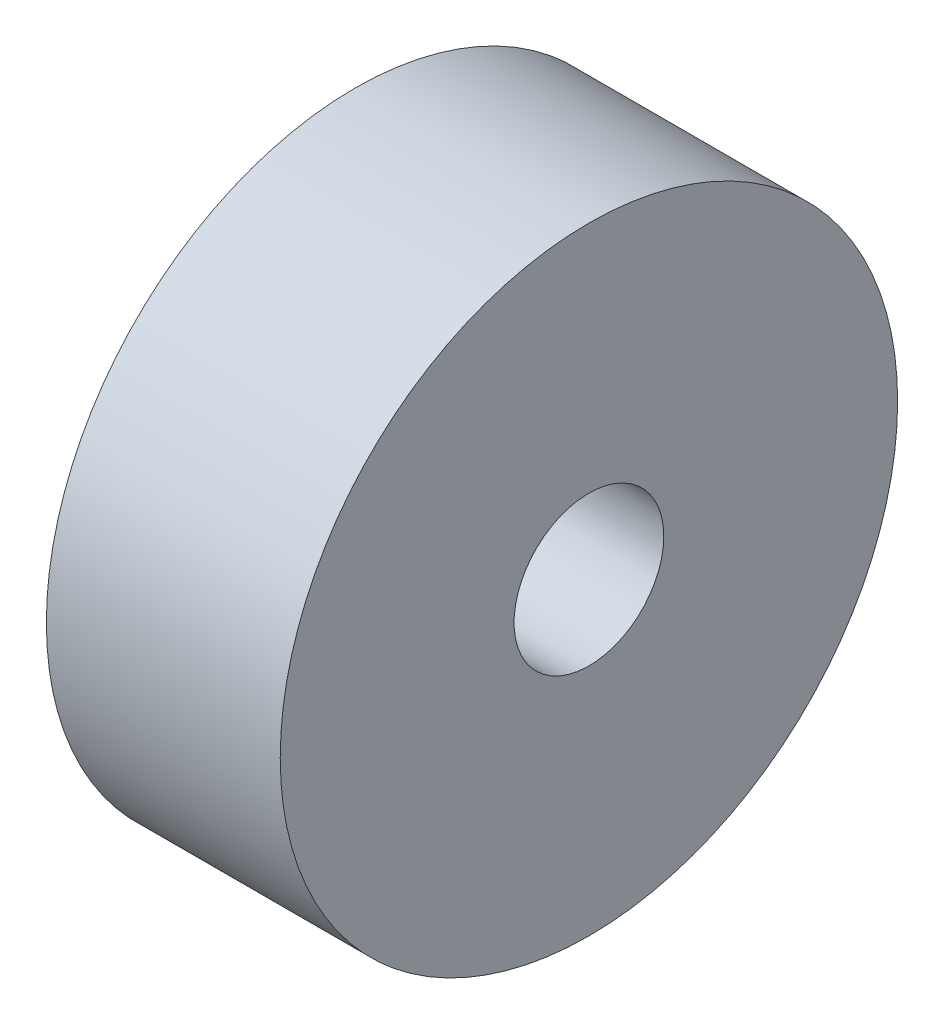
SolidWorks part; units mm, degrees
ref_plane "정면" through (0, 0, 0) normal (0, 0, 1) x (1, 0, 0)
ref_plane "윗면" through (0, 0, 0) normal (0, 1, 0) x (1, 0, 0)
ref_plane "우측면" through (0, 0, 0) normal (1, 0, 0) x (0, 0, -1)
sketch "스케치1" plane through (0, 0, 0) normal (1, 0, 0) x (0, 0, -1)
  circle A0 centre (0, 0) radius 33
extrude "보스-돌출2" add sketch "스케치1" along normal blind 25
sketch "스케치3" plane through (0, 0, 0) normal (1, 0, 0) x (0, 0, -1)
  circle A0 centre (0, 0) radius 8
extrude "컷-돌출3" cut sketch "스케치3" against normal through all and the other way through all
